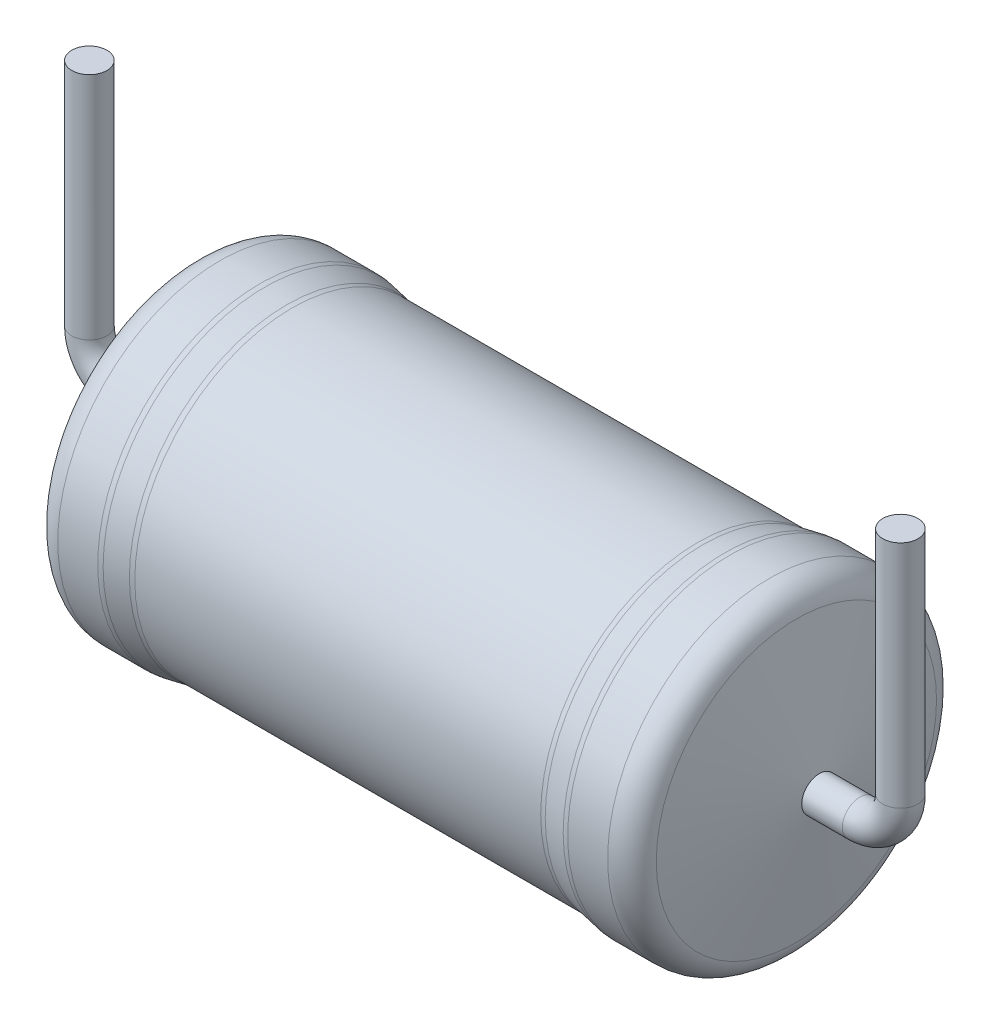
SolidWorks part; units mm, degrees
ref_plane "Front Plane" through (0, 0, 0) normal (0, 0, 1) x (1, 0, 0)
ref_plane "Top Plane" through (0, 0, 0) normal (0, 1, 0) x (1, 0, 0)
ref_plane "Right Plane" through (0, 0, 0) normal (1, 0, 0) x (0, 0, -1)
sketch "Sketch1" plane through (0, 0, 0) normal (0, 0, 1) x (1, 0, 0)
  line L0 (0, 0) -> (6, 0)
  line L1 (6, 0) -> (6, 0.325)
  line L2 (6, 0.325) -> (5.5, 3)
  line L3 (5.5, 3) -> (4.3, 3)
  line L4 (4.3, 3) -> (3.8, 2.9065)
  line L5 (3.8, 2.9065) -> (-3.8, 2.9065)
  line L6 (-3.8, 2.9065) -> (-4.3, 3)
  line L7 (-4.3, 3) -> (-5.5, 3)
  line L8 (-5.5, 3) -> (-6, 0.325)
  line L9 (-6, 0.325) -> (-6, 0)
  line L10 (-6, 0) -> (0, 0)
  point P2 (4.9, 3)
  dimension "D1" = 0.325
  dimension "D2" = 0.325
  dimension "D3" = 6
  dimension "D4" = 6
  dimension "D5" = 3
  dimension "D6" = 3
  dimension "D7" = 0.5
  dimension "D8" = 0.5
  dimension "D9" = 1.2
  dimension "D12" = 0.5
  dimension "D13" = 2.9065
revolve "Revolve1" add sketch "Sketch1" angle 360 about L0
fillet "Fillet1" radius 0.5 6 edges at (-5.5, 0, 3) (-4.3, 0, 3) (-3.8, 0, 2.9065) (3.8, 0, 2.9065) (4.3, 0, 3) (5.5, 0, 3)
sketch "Sketch4" plane through (6, 0, 0) normal (1, 0, 0) x (0, 0, -1)
  circle A0 centre (0, 0) radius 0.325
  circle A1 centre (0, 0) radius 0.325 construction
sketch "Sketch6" plane through (0, 0, 0) normal (0, 0, 1) x (1, 0, 0)
  line L0 (6, 0) -> (6.75, 0)
  line L1 (7.5, 0.75) -> (7.5, 5)
  line L2 (6, 0) -> (-6.75, 0)
  line L3 (-7.5, 0.75) -> (-7.5, 5)
  arc A0 (-6.75, 0) -> (-7.5, 0.75) centre (-6.75, 0.75) cw
  arc A1 (6.75, 0) -> (7.5, 0.75) centre (6.75, 0.75) ccw
  point P8 (-7.5, 0)
  point P11 (7.5, 0)
  dimension "D5" = 0.75
  dimension "D1" = 1.5
  dimension "D2" = 5
  dimension "D3" = 13.5
  dimension "D4" = 5
sweep "Sweep1" add profiles "Sketch4" path "Sketch6"
